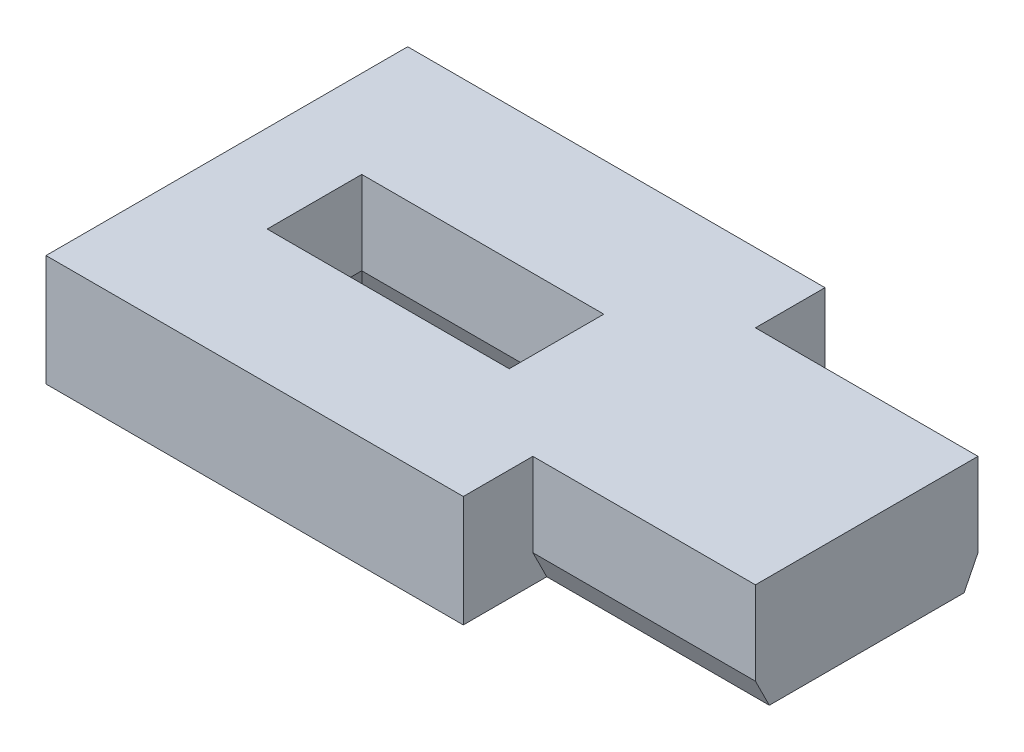
SolidWorks part; units mm, degrees
ref_plane "Front Plane" through (0, 0, 0) normal (0, 0, 1) x (1, 0, 0)
ref_plane "Top Plane" through (0, 0, 0) normal (0, 1, 0) x (1, 0, 0)
ref_plane "Right Plane" through (0, 0, 0) normal (1, 0, 0) x (0, 0, -1)
sketch "Sketch1" plane through (0, 0, 0) normal (0, 1, 0) x (1, 0, 0)
  line L1 (-7.5, 6.5) -> (7.5, 6.5)
  line L2 (-7.5, 6.5) -> (-7.5, -6.5)
  line L3 (-7.5, -6.5) -> (7.5, -6.5)
  line L4 (7.5, 6.5) -> (7.5, -6.5)
  line L6 (4.35, -1.7) -> (-4.35, -1.7)
  line L7 (4.35, -1.7) -> (4.35, 1.7)
  line L8 (4.35, 1.7) -> (-4.35, 1.7)
  line L9 (-4.35, -1.7) -> (-4.35, 1.7)
  point P4 (0, 1.7)
  point P10 (0, 6.5)
  point P11 (-4.35, 0)
  point P12 (-7.5, 0)
  dimension "D1" = 8.7
  dimension "D2" = 3.4
  dimension "D3" = 15
  dimension "D4" = 13
extrude "Boss-Extrude1" add sketch "Sketch1" along normal blind 4
sketch "Sketch2" plane through (0, 0, 0) normal (0, 1, 0) x (1, 0, 0)
  line L0 (7.5, 4) -> (15.5, 4)
  line L1 (7.5, -6.5) -> (7.5, 6.5) construction
  line L2 (15.5, 4) -> (15.5, -4)
  line L3 (15.5, -4) -> (7.5, -4)
  line L4 (7.5, 4) -> (7.5, -4)
  point P6 (7.5, 0)
  point P7 (15.5, 0)
  dimension "D1" = 8
  dimension "D2" = 8
extrude "Boss-Extrude3" add sketch "Sketch2" along normal blind 4
chamfer "Chamfer1" distance 1 distance2 0.5 4 edges at (4.35, 0, 0) (0, 0, 1.7) (-4.35, 0, 0) (0, 0, -1.7)
chamfer "Chamfer2" distance 0.5 distance2 1 2 edges at (11.5, 0, 4) (11.5, 0, -4)
